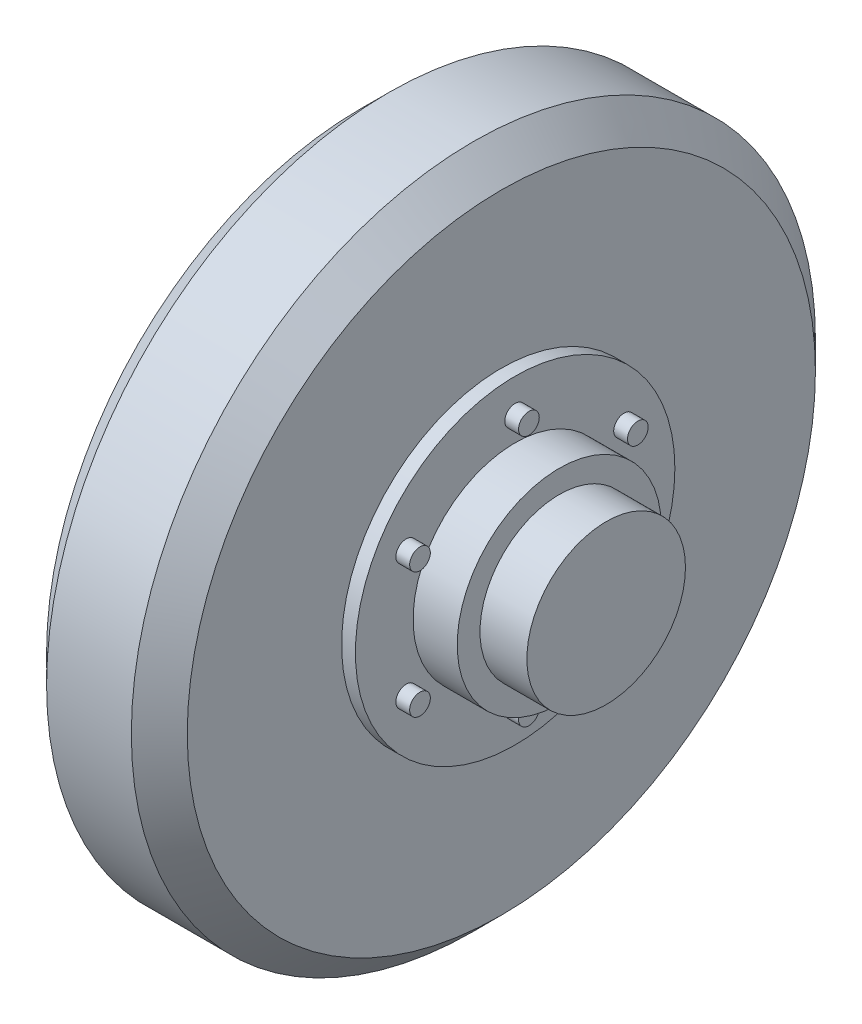
SolidWorks part; units mm, degrees
ref_plane "Front Plane" through (0, 0, 0) normal (1, 0, 0) x (0, 1, 0)
ref_plane "Top Plane" through (0, 0, 0) normal (0, 0, 1) x (0, 1, 0)
ref_plane "Right Plane" through (0, 0, 0) normal (0, 1, 0) x (-1, 0, 0)
sketch "Sketch1" plane through (0, 0, 0) normal (0, 1, 0) x (-1, 0, 0)
  line L0 (0, 73.5501) -> (6.35, 73.5501)
  line L1 (0, 0) -> (71.12, 0)
  line L2 (0, 0) -> (0, 157.48)
  line L3 (0, 157.48) -> (71.12, 157.48)
  line L4 (71.12, 0) -> (71.12, 157.48)
  line L5 (6.35, 73.5501) -> (6.35, 144.6057)
  line L6 (6.35, 144.6057) -> (19.2243, 157.48)
  line L7 (58.2457, 157.48) -> (71.12, 144.6057)
  line L9 (0, 0) -> (-20.32, 0)
  line L10 (0, 0) -> (0, 46.99)
  line L11 (0, 46.99) -> (-20.32, 46.99)
  line L12 (-20.32, 0) -> (-20.32, 46.99)
  line L13 (71.12, 0) -> (83.82, 0)
  line L14 (71.12, 0) -> (71.12, 14.9987)
  line L15 (71.12, 14.9987) -> (83.82, 14.9987)
  line L16 (83.82, 0) -> (83.82, 14.9987)
  line L17 (83.82, 0) -> (90.17, 0)
  line L18 (83.82, 0) -> (83.82, 24.13)
  line L19 (83.82, 24.13) -> (90.17, 24.13)
  line L20 (90.17, 0) -> (90.17, 24.13)
  line L21 (-20.32, 0) -> (-41.91, 0)
  line L22 (-20.32, 0) -> (-20.32, 36.5125)
  line L23 (-20.32, 36.5125) -> (-41.91, 36.5125)
  line L24 (-41.91, 0) -> (-41.91, 36.5125)
  dimension "D1" = 157.48
  dimension "D2" = 71.12
  dimension "D3" = 12.7
  dimension "D4" = 6.35
  dimension "D5" = 14.9987
  dimension "D6" = 24.13
  dimension "D7" = 20.32
  dimension "D8" = 45
  dimension "D9" = 45
  dimension "D10" = 6.35
  dimension "D11" = 46.99
  dimension "D13" = 36.5125
  dimension "D14" = 132.08
revolve "Revolve1" add sketch "Sketch1" angle 360 about L1
sketch "Sketch2" plane through (-71.12, 0, 0) normal (-1, 0, 0) x (0, -1, 0)
  line L1 (0, -38.1) -> (36.2353, -11.7735)
  line L2 (36.2353, -11.7735) -> (22.3946, 30.8235)
  line L3 (22.3946, 30.8235) -> (-22.3946, 30.8235)
  line L4 (-22.3946, 30.8235) -> (-36.2353, -11.7735)
  line L5 (-36.2353, -11.7735) -> (0, -38.1)
  circle A0 centre (0, 0) radius 38.1
  circle A1 centre (0, 0) radius 144.6057
  circle A2 centre (0, 0) radius 144.6057
  circle A3 centre (0, 0) radius 30.8235 construction
  point P1 (-20.6586, 32.013)
  point P11 (0, -38.1)
  dimension "D2" = 76.2
  dimension "D1" = 0
sketch "Sketch3" plane through (-71.12, 0, 0) normal (-1, 0, 0) x (0, -1, 0)
  circle A0 centre (-22.3946, 30.8235) radius 3.3734
  circle A1 centre (22.3946, 30.8235) radius 3.3734
  circle A2 centre (36.2353, -11.7735) radius 3.3734
  circle A3 centre (0, -38.1) radius 3.3734
  circle A4 centre (-36.2353, -11.7735) radius 3.3734
  point P0 (-36.2353, -11.7735)
  point P2 (0, -38.1)
  point P4 (36.2353, -11.7735)
  point P6 (22.3946, 30.8235)
  point P8 (-22.3946, 30.8235)
  dimension "D1" = 6.7469
extrude "Cut-Extrude1" cut sketch "Sketch3" against normal blind 11.43
sketch "Sketch4" plane through (0, 0, 0) normal (1, 0, 0) x (0, 1, 0)
  line L0 (28.956, -50.1533) -> (57.912, 0)
  line L1 (57.912, 0) -> (28.956, 50.1533)
  line L2 (28.956, 50.1533) -> (-28.956, 50.1533)
  line L3 (-28.956, 50.1533) -> (-57.912, 0)
  line L4 (-57.912, 0) -> (-28.956, -50.1533)
  line L5 (-28.956, -50.1533) -> (28.956, -50.1533)
  circle A0 centre (0, 0) radius 50.1533 construction
  circle A1 centre (0, 0) radius 73.5501
  circle A2 centre (0, 0) radius 73.5501
  circle A3 centre (28.956, 50.1533) radius 4.7625
  dimension "D3" = 9.525
  dimension "D2" = 115.824
  dimension "D1" = 0
sketch "Sketch5" plane through (0, 0, 0) normal (1, 0, 0) x (0, 1, 0)
  circle A0 centre (28.956, 50.1533) radius 4.7625 construction
  circle A1 centre (28.956, 50.1533) radius 4.7625
  circle A2 centre (-28.956, 50.1533) radius 4.7625
  circle A3 centre (-57.912, 0) radius 4.7625
  circle A4 centre (-28.956, -50.1533) radius 4.7625
  circle A5 centre (28.956, -50.1533) radius 4.7625
  circle A6 centre (57.912, 0) radius 4.7625
  point P0 (28.956, -50.1533)
  point P2 (57.912, 0)
  point P4 (28.956, 50.1533)
  point P9 (-28.956, -50.1533)
  point P11 (-57.912, 0)
  point P13 (-28.956, 50.1533)
extrude "Boss-Extrude1" add sketch "Sketch5" along normal blind 6.35
equation "\"D9@Sketch1\"=\"D8@Sketch1\""
